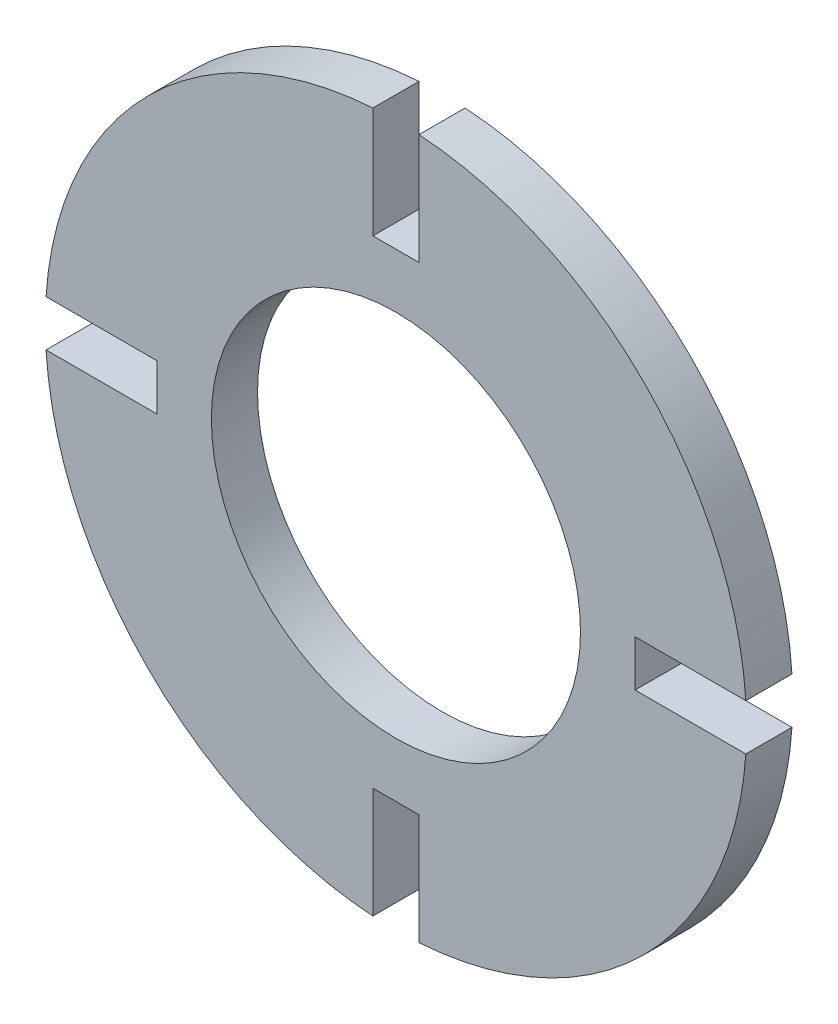
SolidWorks part; units mm, degrees
material "Balsa"
ref_plane "Front Plane" through (0, 0, 0) normal (0, 0, 1) x (1, 0, 0)
ref_plane "Top Plane" through (0, 0, 0) normal (0, 1, 0) x (1, 0, 0)
ref_plane "Right Plane" through (0, 0, 0) normal (1, 0, 0) x (0, 0, -1)
sketch "Sketch1" plane through (0, 0, 0) normal (0, 0, 1) x (1, 0, 0)
  line L1 (2.5, 37.9177) -> (2.5, 25.9177)
  line L2 (2.5, 25.9177) -> (-2.5, 25.9177)
  line L3 (-2.5, 25.9177) -> (-2.5, 37.9177)
  line L4 (25.9177, -2.5) -> (25.9177, 2.5)
  line L5 (37.9177, -2.5) -> (25.9177, -2.5)
  line L6 (25.9177, 2.5) -> (37.9177, 2.5)
  line L7 (-2.5, -25.9177) -> (2.5, -25.9177)
  line L8 (-2.5, -37.9177) -> (-2.5, -25.9177)
  line L9 (2.5, -25.9177) -> (2.5, -37.9177)
  line L10 (-25.9177, 2.5) -> (-25.9177, -2.5)
  line L11 (-37.9177, 2.5) -> (-25.9177, 2.5)
  line L12 (-25.9177, -2.5) -> (-37.9177, -2.5)
  arc A0 (-2.5, 37.9177) -> (-37.9177, 2.5) centre (0, 0) ccw
  circle A1 centre (0, 0) radius 20
  arc A2 (37.9177, 2.5) -> (2.5, 37.9177) centre (0, 0) ccw
  arc A3 (2.5, -37.9177) -> (37.9177, -2.5) centre (0, 0) ccw
  arc A4 (-37.9177, -2.5) -> (-2.5, -37.9177) centre (0, 0) ccw
  point P1 (0, 25.9177)
  point P7 (0, 38)
  point P23 (0, 0)
  dimension "D1" = 76
  dimension "D2" = 40
  dimension "D3" = 5
  dimension "D4" = 4
  dimension "D5" = 12
extrude "Boss-Extrude1" add sketch "Sketch1" along normal blind 5
